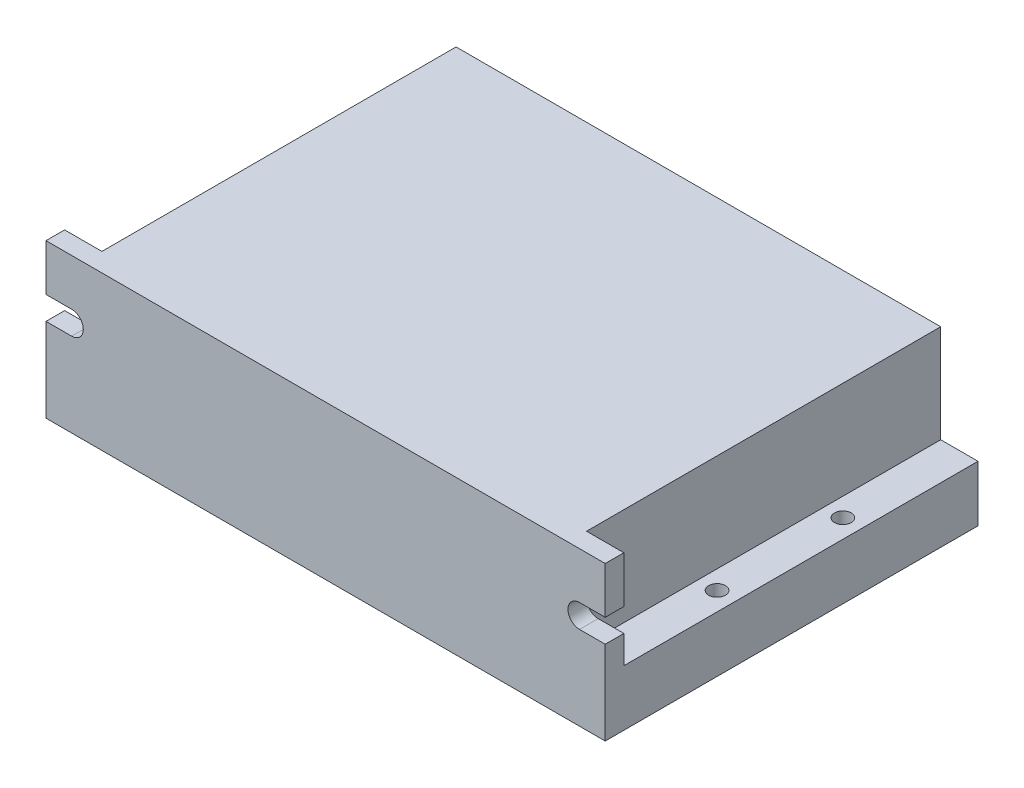
SolidWorks part; units mm, degrees
ref_plane "Front Plane" through (0, 0, 0) normal (0, 0, 1) x (1, 0, 0)
ref_plane "Top Plane" through (0, 0, 0) normal (0, 1, 0) x (1, 0, 0)
ref_plane "Right Plane" through (0, 0, 0) normal (1, 0, 0) x (0, 0, -1)
sketch "Sketch1" plane through (0, 0, 0) normal (0, 1, 0) x (1, 0, 0)
  line L1 (-60, 40) -> (60, 40)
  line L2 (-60, 40) -> (-60, -40)
  line L3 (-60, -40) -> (60, -40)
  line L4 (60, 40) -> (60, -40)
  line L5 (-60, 40) -> (60, -40) construction
  line L6 (-60, -40) -> (60, 40) construction
  point P0 (0, 0)
  dimension "D1" = 120
  dimension "D2" = 80
extrude "Boss-Extrude1" add sketch "Sketch1" along normal blind 33
sketch "Sketch2" plane through (0, 33, 0) normal (0, 1, 0) x (1, 0, 0)
  line L0 (-60, -40) -> (60, -40) construction
  line L1 (-60, 40) -> (-52, 40)
  line L2 (-60, 40) -> (-60, -36)
  line L3 (-60, -36) -> (-52, -36)
  line L4 (-52, 40) -> (-52, -36)
  dimension "D1" = 8
  dimension "D2" = 4
extrude "Cut-Extrude1" cut sketch "Sketch2" against normal offset from surface (21 mm away) 12 up to face at (0, 0, 0)
sketch "Sketch3" plane through (0, 12, 0) normal (0, 1, 0) x (1, 0, 0)
  line L0 (-56, 15) -> (-56, -12) construction
  line L1 (-60, -36) -> (-60, 40) construction
  line L3 (-60, 40) -> (-52, 40) construction
  circle A0 centre (-56, 15) radius 1.8
  circle A1 centre (-56, -12) radius 1.8
  dimension "D1" = 27
  dimension "D2" = 3.6
  dimension "D3" = 4
  dimension "D4" = 25
extrude "Cut-Extrude2" cut sketch "Sketch3" against normal through all
sketch "Sketch4" plane through (0, 0, 40) normal (0, 0, 1) x (1, 0, 0)
  line L0 (-60, 23) -> (-54.5, 23)
  line L1 (-60, 33) -> (-60, 0) construction
  line L2 (-60, 18) -> (-54.5, 18)
  line L3 (-60, 33) -> (60, 33) construction
  circle A0 centre (-54.5, 20.5) radius 2.5
  line M6 (-60, 33) -> (-60, 0)
  dimension "D1" = 5
  dimension "D2" = 10
  dimension "D3" = 5.5
extrude "Cut-Extrude3" cut sketch "Sketch4" against normal through all contours A0 | A0 L0 L2 M6
mirror "Mirror1" about plane through (0, 0, 0) normal (1, 0, 0) of "Cut-Extrude3", "Cut-Extrude1", "Cut-Extrude2"
